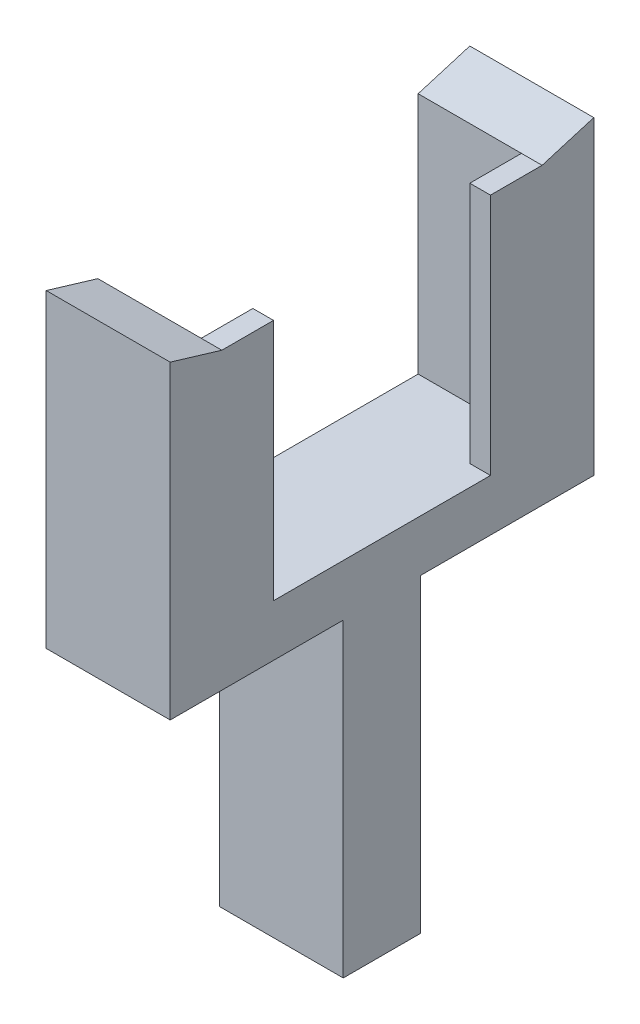
SolidWorks part; units mm, degrees
ref_plane "Front Plane" through (0, 0, 0) normal (0, 0, 1) x (1, 0, 0)
ref_plane "Top Plane" through (0, 0, 0) normal (0, 1, 0) x (1, 0, 0)
ref_plane "Right Plane" through (0, 0, 0) normal (1, 0, 0) x (0, 0, -1)
sketch "Sketch1" plane through (0, 0, 0) normal (1, 0, 0) x (0, 0, -1)
  line L0 (0, 22.7228) -> (0, -18.3997) construction
  line L1 (-3.75, -29.3588) -> (-3.75, 0.6412)
  line L2 (-3.75, 0.6412) -> (-20.5, 0.6412)
  line L3 (-20.5, 0.6412) -> (-20.5, 30.6412)
  line L5 (-15.5, 29.1412) -> (-15.5, 5.6412)
  line L6 (-15.5, 5.6412) -> (15.5, 5.6412)
  line L7 (3.75, -29.3588) -> (3.75, 0.6412)
  line L8 (-3.75, -29.3588) -> (3.75, -29.3588)
  line L10 (15.5, 29.1412) -> (15.5, 5.6412)
  line L11 (3.75, 0.6412) -> (20.5, 0.6412)
  line L15 (20.5, 0.6412) -> (20.5, 30.6412)
  line L16 (-20.5, 30.6412) -> (-15.5, 29.1412)
  line L17 (20.5, 30.6412) -> (15.5, 29.1412)
  point P16 (0, 5.6412)
  dimension "D1" = 31
  dimension "D2" = 7.5
  dimension "D3" = 5
  dimension "D4" = 23.5
  dimension "D6" = 30
  dimension "D7" = 30
extrude "Boss-Extrude1" add sketch "Sketch1" along normal mid plane 12
sketch "Sketch2" plane through (0, 0, 15.5) normal (0, 0, -1) x (-1, 0, 0)
  line L1 (-6, 29.1412) -> (-4, 29.1412)
  line L2 (-6, 29.1412) -> (-6, 5.6412)
  line L3 (-6, 5.6412) -> (-4, 5.6412)
  line L4 (-4, 29.1412) -> (-4, 5.6412)
  dimension "D1" = 2
extrude "Boss-Extrude2" add sketch "Sketch2" along normal blind 5
ref_plane "Plane1" through (0, 0, 0) normal (0, 0, -1) x (-1, 0, 0)
mirror "Mirror1" about plane through (0, 0, 0) normal (0, 0, -1) of "Boss-Extrude2"
